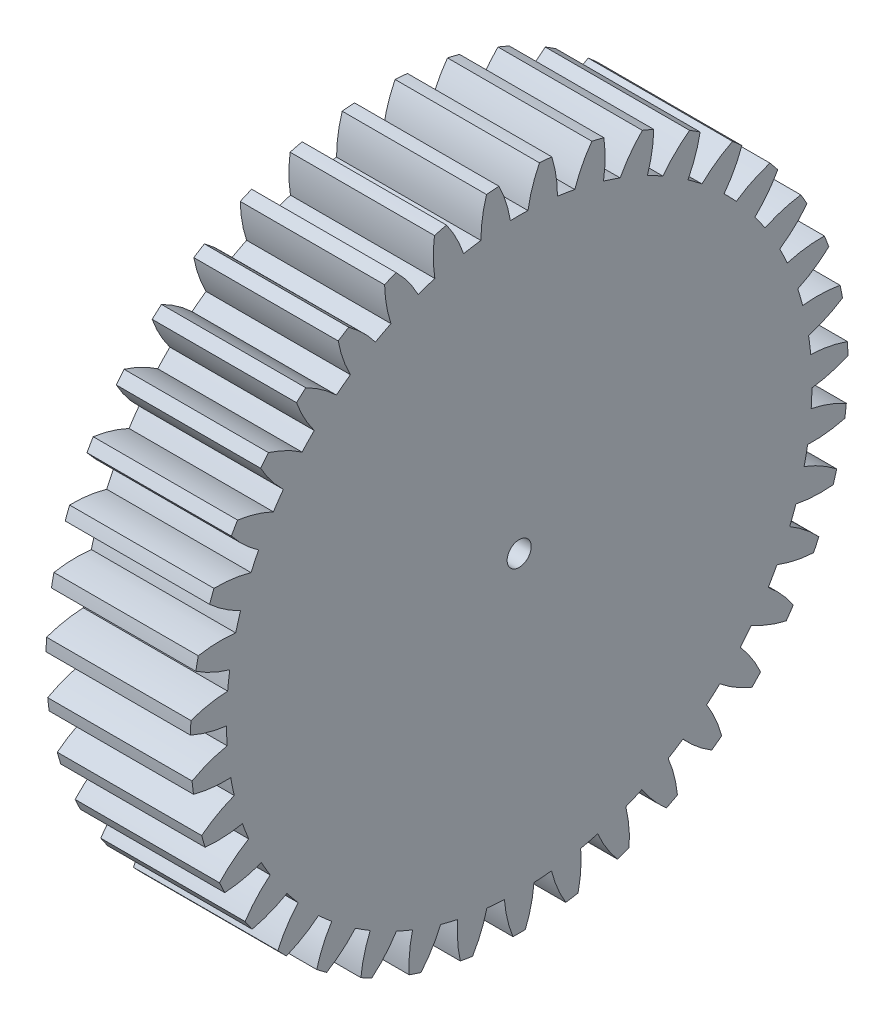
SolidWorks part; units mm, degrees
ref_plane "Plane1" through (0, 0, 0) normal (0, 0, 1) x (1, 0, 0)
ref_plane "Plane2" through (0, 0, 0) normal (0, 1, 0) x (1, 0, 0)
ref_plane "Plane3" through (0, 0, 0) normal (1, 0, 0) x (0, 0, -1)
sketch "HoldingSke" plane through (0, 0, 0) normal (0, 1, 0) x (1, 0, 0)
  line L0 (0, 0) -> (236.8741, -191.8169)
  line L1 (-15, 0) -> (100, 0) construction
  line L2 (0, 0) -> (-2.1039, 2.3779)
  line L3 (0, 0) -> (-11.863, 4.5341)
  line L4 (0, 0) -> (6.7114, 5.4348)
  line L5 (0, 0) -> (-47.5972, -17.7524)
  line L6 (0, 0) -> (-15.7917, -10.6547)
  line L7 (-2.1039, 2.3779) -> (8.8308, 51.9871)
  line L8 (-76.2, 54.61) -> (-72.771, 54.61)
  line L9 (-67.7845, 28.3722) -> (-49.3413, 33.142)
  line L10 (-76.2, 71.12) -> (104.1128, 71.12)
  line L11 (0, 0) -> (-19.05, 0)
  line L12 (-76.2, 101.6) -> (-76.1147, 101.6)
  line L13 (24.9733, 27.94) -> (52.9518, 28.4284)
  line L14 (24.9733, 27.94) -> (24.9746, 27.94)
  line L15 (24.9733, 27.94) -> (100.4006, 29.5858)
  circle A0 centre (0, 0) radius 1.5875
  circle A1 centre (0, 0) radius 38.1
  circle A2 centre (0, 0) radius 38.1
  circle A3 centre (0, 0) radius 1.5875
  dimension "MHD" = 76.2
  dimension "Hub_dia" = 76.2
  dimension "Bore" = 3.175
  dimension "MBD" = 3.175
  dimension "Num_teeth" = 39
  dimension "Pitch" = 304.8
  dimension "Overall_len" = 50.8
  dimension "Show_teeth" = 39
  dimension "Thickness" = 19.05
  dimension "OAL" = 50.8001
  dimension "T_dim" = 3.429
  dimension "Ap" = 14.5
  dimension "H" = 19.05
  dimension "Pitch_radius" = 180.3128
  dimension "Width" = 19.05
  dimension "Backlash" = 0.0853
  dimension "Addendum_fac" = 1
  dimension "Dedendum_fac" = 1.25
  dimension "Clearance_fac" = 0.25
  dimension "Dedendum_add" = 0.0013
sketch "BasProSke" plane through (0, 0, 0) normal (0, 1, 0) x (1, 0, 0)
  line L0 (-10, 0) -> (60, 0) construction
  line L1 (0, 0) -> (0, 43.3917)
  line L2 (0, 0) -> (19.05, 0)
  line L3 (19.05, 0) -> (19.05, 43.3917)
  line L4 (19.05, 43.3917) -> (0, 43.3917)
  dimension "Thickness" = 19.05
  dimension "Diameter" = 86.7833
revolve "Base-Revolve" add sketch "BasProSke" angle 360 about L0
sketch "TooCutSke" plane through (0, 0, 0) normal (1, 0, 0) x (0, 0, -1)
  line L1 (0, 0) -> (0, 107) construction
  line L2 (0, 0) -> (-1.8113, 41.2352) construction
  line L3 (0, 0) -> (-6.6381, 82.227) construction
  line L4 (-1.8113, 41.2352) -> (-3.319, 41.1135) construction
  arc A0 (1.1579, 38.6105) -> (-1.1579, 38.6105) centre (0, 0) ccw
  arc A1 (2.686, 43.3339) -> (-2.686, 43.3339) centre (0, 0) ccw
  circle A2 centre (0, 0) radius 41.275 construction
  circle A3 centre (0, 0) radius 39.9603 construction
  arc A4 (-1.1579, 38.6105) -> (-2.686, 43.3339) centre (-17.4518, 35.948) ccw
  arc A5 (2.686, 43.3339) -> (1.1579, 38.6105) centre (17.4518, 35.948) ccw
  dimension "Root_dia" = 77.2558
  dimension "Overcut_dia" = 86.8341
  dimension "Pitch_dia" = 82.55
  dimension "Base_dia" = 79.9206
  dimension "Flank_rad" = 16.51
  dimension "Half_ang" = 4.615
  dimension "Half_CT" = 1.5126
extrude "ToothCut" cut sketch "TooCutSke" along normal through all
fillet "Breaks" [suppressed] radius 0.0423
fillet "RootFillets" [suppressed] radius 0.5304
pattern_circular "TeethCuts" count 39 every 9.231 about axis through (-10, 0, 0) along (1, 0, 0) of "ToothCut", "RootFillets", "Breaks"
sketch "HubNeaOneSke" plane through (0, 0, 0) normal (-1, 0, 0) x (0, 0, 1)
  circle A0 centre (0, 0) radius 38.1
  dimension "Diameter" = 76.2
extrude "HubNearOne" [suppressed] add sketch "HubNeaOneSke" along normal blind 31.7501
sketch "HubNeaBotSke" plane through (0, 0, 0) normal (-1, 0, 0) x (0, 0, 1)
  circle A0 centre (0, 0) radius 38.1
  dimension "Diameter" = 76.2
extrude "HubNearBoth" [suppressed] add sketch "HubNeaBotSke" along normal blind 15.875
ref_plane "FarPln" through (19.05, 0, 0) normal (1, 0, 0) x (0, 0, -1)
sketch "HubFarSke" plane through (19.05, 0, 0) normal (1, 0, 0) x (0, 0, -1)
  circle A0 centre (0, 0) radius 38.1
  dimension "Diameter" = 76.2
extrude "HubFar" [suppressed] add sketch "HubFarSke" along normal blind 15.875
sketch "BorSke" plane through (0, 0, 0) normal (1, 0, 0) x (0, 0, -1)
  circle A0 centre (0, 0) radius 1.5875
  dimension "Diameter" = 3.175
extrude "Bore" cut sketch "BorSke" along normal mid plane 101.6001
sketch "KeySke" plane through (0, 0, 0) normal (1, 0, 0) x (0, 0, -1)
  line L0 (-0.127, 0) -> (-0.127, 1.8415)
  line L1 (-0.127, 1.8415) -> (0.127, 1.8415)
  line L2 (0.127, 1.8415) -> (0.127, 0)
  line L3 (0, 0) -> (0, 34) construction
  line L4 (-0.127, 0) -> (0.127, 0)
  dimension "Offset" = 1.8415
  dimension "Width" = 0.254
extrude "Keyway" [suppressed] cut sketch "KeySke" along normal mid plane 101.6001
pattern_circular "Keyway2" [suppressed] count 2 every 90 about axis through (-10, 0, 0) along (1, 0, 0)
equation "' \"Pitch@HoldingSke\" = 4"
equation "' \"Num_teeth@HoldingSke\" = 12"
equation "' \"Ap@HoldingSke\" =  20"
equation "' \"Ap@HoldingSke\" = 20"
equation "' \"Width@HoldingSke\" = 0.5"
equation "' \"Hub_dia@HoldingSke\"= 1"
equation "' \"Hub_dia@HoldingSke\" = 1"
equation "' \"Overall_len@HoldingSke\" = 1.0"
equation "' \"Bore@HoldingSke\" = 0.75"
equation "' \"T_dim@HoldingSke\" = 0.85"
equation "' \"Width@KeySke\" = 0.25"
equation "' \"Show_teeth@HoldingSke\" = 13"
equation "' \"Backlash@HoldingSke\" = 0.009"
equation "' \"Addendum_fac@HoldingSke\" = 1.0"
equation "' \"Dedendum_fac@HoldingSke\" = 1.25"
equation "' \"Dedendum_add@HoldingSke\" = 0.00005"
equation "' \"Clearance_fac@HoldingSke\" = 0.25"
equation "' \"Pitch@HoldingSke\" = 0.5"
equation "' \"Num_teeth@HoldingSke\" = 23"
equation "' \"Show_teeth@HoldingSke\" = 23"
equation "' \"Backlash@HoldingSke\" = 0.0375"
equation "\"Overcut_dia@TooCutSke\" = (\"Num_teeth@HoldingSke\" + 2 * \"Addendum_fac@HoldingSke\") / \"Pitch@HoldingSke\" + 0.002"
equation "\"Pitch_dia@TooCutSke\" = \"Num_teeth@HoldingSke\" / \"Pitch@HoldingSke\""
equation "\"Base_dia@TooCutSke\" = \"Num_teeth@HoldingSke\" / \"Pitch@HoldingSke\" * cos((\"Ap@HoldingSke\"  * 3.14159265 / 180))"
equation "\"Root_dia@TooCutSke\" = (\"Num_teeth@HoldingSke\" + 2) / \"Pitch@HoldingSke\" - 2 * (\"Addendum_fac@HoldingSke\" + \"Dedendum_fac@HoldingSke\") / \"Pitch@HoldingSke\" - \"Dedendum_add@HoldingSke\" * 2"
equation "\"Half_ang@TooCutSke\" = 180 / \"Num_teeth@HoldingSke\""
equation "\"Half_CT@TooCutSke\" = \"Num_teeth@HoldingSke\" / \"Pitch@HoldingSke\" * sin((3.14159265 / 2 / \"Num_teeth@HoldingSke\")) / 2 - 7 * \"Backlash@HoldingSke\" / 4"
equation "\"Flank_rad@TooCutSke\" = \"Num_teeth@HoldingSke\" / \"Pitch@HoldingSke\" / 5"
equation "\"Radius@RootFillets\" = \"Clearance_fac@HoldingSke\" / \"Pitch@HoldingSke\" + \"Dedendum_add@HoldingSke\""
equation "\"Break_rad@Breaks\" = 0.02 / \"Pitch@HoldingSke\""
equation "\"Thickness@HoldingSke\" = \"Width@HoldingSke\""
equation "\"OAL@HoldingSke\" = \"Thickness@HoldingSke\""
equation "\"MHD@HoldingSke\" = (\"Num_teeth@HoldingSke\" + 2) / \"Pitch@HoldingSke\" - 2 * (\"Addendum_fac@HoldingSke\" + \"Dedendum_fac@HoldingSke\")  / \"Pitch@HoldingSke\" - \"Dedendum_add@HoldingSke\" * 2"
equation "\"MBD@HoldingSke\" = (\"Num_teeth@HoldingSke\" + 2) / \"Pitch@HoldingSke\" - 2 * (\"Addendum_fac@HoldingSke\" + \"Dedendum_fac@HoldingSke\")  / \"Pitch@HoldingSke\" - \"Dedendum_add@HoldingSke\" * 2 - 0.002"
equation "\"MHD@HoldingSke\" = ((sgn( \"MHD@HoldingSke\" - \"Hub_dia@HoldingSke\" )-1)*( \"MHD@HoldingSke\" - \"Hub_dia@HoldingSke\" ))/-2+ \"Hub_dia@HoldingSke\""
equation "\"MBD@HoldingSke\" = ((sgn( \"MBD@HoldingSke\" - \"Bore@HoldingSke\" )-1)*( \"MBD@HoldingSke\" - \"Bore@HoldingSke\" ))/-2+ \"Bore@HoldingSke\""
equation "\"OAL@HoldingSke\" = ((sgn( \"OAL@HoldingSke\" - \"Overall_len@HoldingSke\" )+1)*( \"OAL@HoldingSke\" - \"Overall_len@HoldingSke\" ))/2 + \"Overall_len@HoldingSke\" + 0.000002"
equation "\"Num_teeth@TeethCuts\" = int( \"Show_teeth@HoldingSke\" ) + 1"
equation "\"Num_teeth@TeethCuts\" = ((sgn( \"Num_teeth@TeethCuts\" - \"Num_teeth@HoldingSke\" )-1)*( \"Num_teeth@TeethCuts\" - \"Num_teeth@HoldingSke\" ))/-2+ \"Num_teeth@HoldingSke\""
equation "\"Num_teeth@TeethCuts\" = ((sgn( \"Num_teeth@TeethCuts\" - 2.0)+1)*( \"Num_teeth@TeethCuts\" - 2.0))/2 +2.0"
equation "\"Angle@TeethCuts\" = 360.0 / \"Num_teeth@HoldingSke\""
equation "\"Diameter@BasProSke\" = (\"Num_teeth@HoldingSke\" + 2 * \"Addendum_fac@HoldingSke\") / \"Pitch@HoldingSke\""
equation "\"Thickness@BasProSke\"  = \"Thickness@HoldingSke\""
equation "' \"Fillet_rad@BasProSke\" =  \"Thickness@HoldingSke\" * 0.05"
equation "' \"Fillet_rad@BasProSke\" = \"Thickness@HoldingSke\" * 0.05"
equation "\"MHD@HoldingSke\" = ((sgn( \"MHD@HoldingSke\" - \"Root_dia@TooCutSke\" )-1)*( \"MHD@HoldingSke\" - \"Root_dia@TooCutSke\" ))/-2+ \"Root_dia@TooCutSke\""
equation "\"Diameter@HubNeaOneSke\" = \"MHD@HoldingSke\""
equation "\"Length@HubNearOne\" = \"OAL@HoldingSke\" - \"Thickness@BasProSke\""
equation "\"Diameter@HubNeaBotSke\" = \"MHD@HoldingSke\""
equation "\"Length@HubNearBoth\" = ( \"OAL@HoldingSke\" - \"Thickness@BasProSke\" ) / 2.0"
equation "\"Thickness@FarPln\" = \"Thickness@BasProSke\""
equation "\"Diameter@HubFarSke\" = \"MHD@HoldingSke\""
equation "\"Length@HubFar\" = ( \"OAL@HoldingSke\" - \"Thickness@BasProSke\" ) / 2.0"
equation "\"Diameter@BorSke\" = \"MBD@HoldingSke\""
equation "\"D1@Bore\" = \"OAL@HoldingSke\" * 2.0"
equation "\"D1@Keyway\" = \"OAL@HoldingSke\" * 2.0"
equation "\"Offset@KeySke\" = \"T_dim@HoldingSke\" - \"MBD@HoldingSke\" / 2.0"
